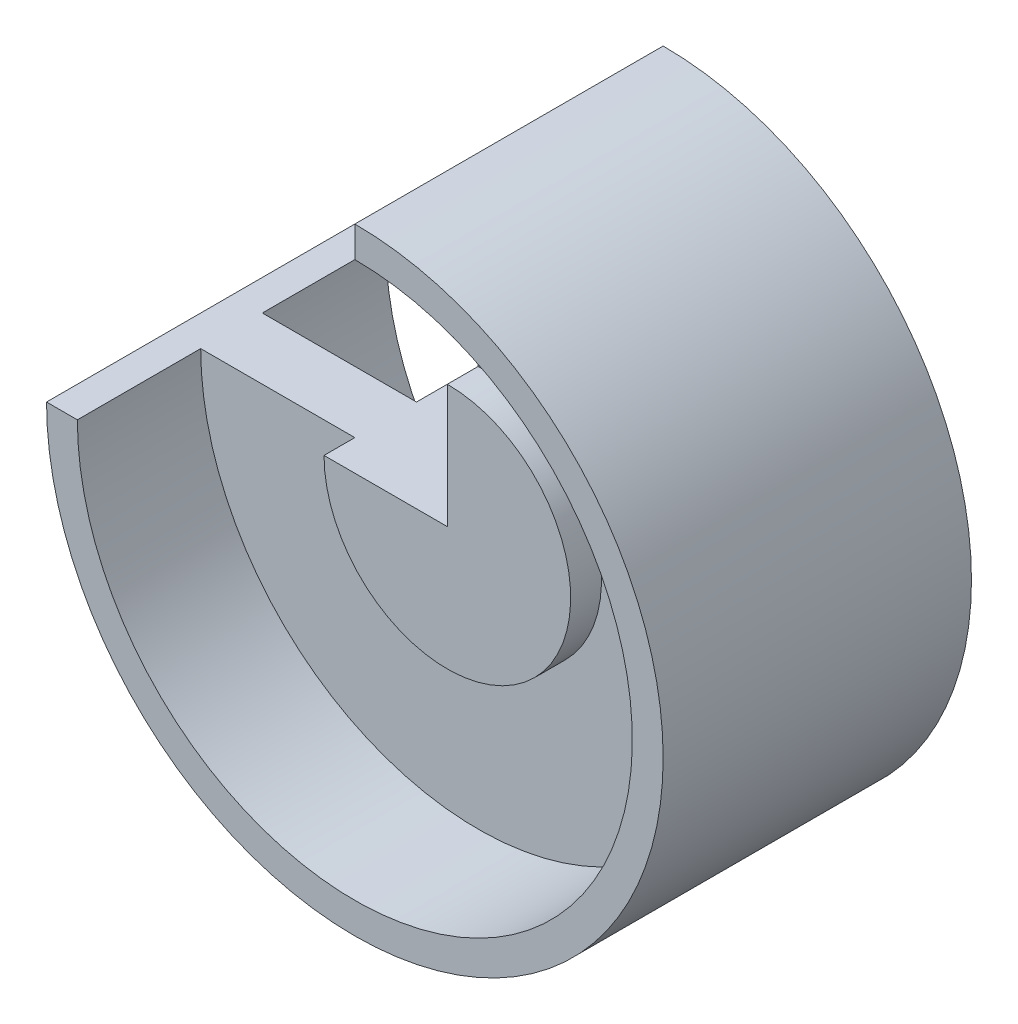
SolidWorks part; units mm, degrees
ref_plane "Front Plane" through (0, 0, 0) normal (0, 0, 1) x (1, 0, 0)
ref_plane "Top Plane" through (0, 0, 0) normal (0, 1, 0) x (1, 0, 0)
ref_plane "Right Plane" through (0, 0, 0) normal (1, 0, 0) x (0, 0, -1)
sketch "Sketch1" plane through (0, 0, 0) normal (1, 0, 0) x (0, 0, -1)
  line L0 (0, 0) -> (0, 12777.2447) construction
  line L1 (0, 0) -> (12777.2447, 0) construction
  line L2 (-10, 0) -> (10, 0)
  line L3 (10, 0) -> (10, 20)
  line L4 (10, 20) -> (5, 20)
  line L5 (5, 20) -> (5, 45)
  line L6 (5, 45) -> (25, 45)
  line L7 (25, 45) -> (25, 50)
  line L8 (-25, 45) -> (-25, 50)
  line L9 (-5, 45) -> (-25, 45)
  line L10 (-5, 20) -> (-5, 45)
  line L11 (-10, 20) -> (-5, 20)
  line L12 (-10, 0) -> (-10, 20)
  line L13 (-25, 50) -> (25, 50)
  point P8 (0, 0)
  dimension "D1" = 20
  dimension "D2" = 20
  dimension "D3" = 25
  dimension "D4" = 5
  dimension "D5" = 50
  dimension "D6" = 10
revolve "Revolve16" add sketch "Sketch1" angle 270 about L1
